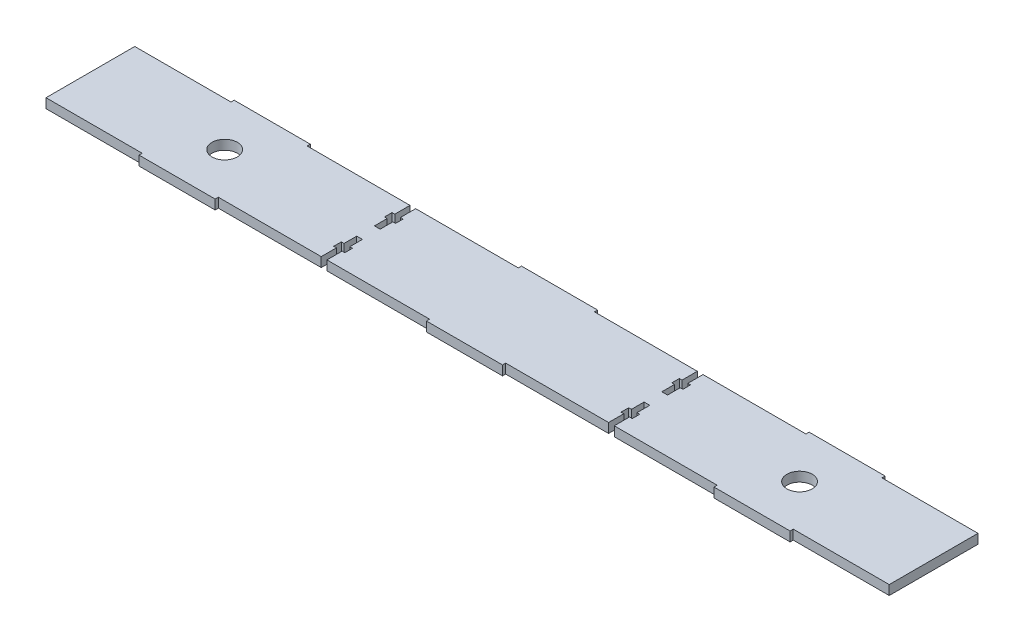
SolidWorks part; units mm, degrees
other "Markup1"
sketch "Sketch5" plane through (-211.1375, 0, -23.8125) normal (0, -1, 0) x (1, 0, 0)
ref_plane "Front Plane" through (0, 0, 0) normal (0, 0, 1) x (1, 0, 0)
ref_plane "Top Plane" through (0, 0, 0) normal (0, 1, 0) x (1, 0, 0)
ref_plane "Right Plane" through (0, 0, 0) normal (1, 0, 0) x (0, 0, -1)
sketch "Sketch1" plane through (0, 0, 0) normal (0, 1, 0) x (1, 0, 0)
  line L1 (214.3125, -23.8125) -> (-214.3125, -23.8125)
  line L2 (214.3125, -23.8125) -> (214.3125, 23.8125)
  line L3 (214.3125, 23.8125) -> (-214.3125, 23.8125)
  line L4 (-214.3125, -23.8125) -> (-214.3125, 23.8125)
  line L5 (214.3125, -23.8125) -> (-214.3125, 23.8125) construction
  line L6 (214.3125, 23.8125) -> (-214.3125, -23.8125) construction
  point P0 (0, 0)
  dimension "D1" = 428.625
  dimension "D2" = 47.625
extrude "Boss-Extrude1" add sketch "Sketch1" along normal blind 4.7625
sketch "Sketch2" plane through (0, 0, 0) normal (0, -1, 0) x (1, 0, 0)
  line L0 (74.1204, -22.225) -> (70.1516, -22.225) construction
  line L1 (-69.8976, -22.225) -> (-73.8664, -22.225) construction
  line L2 (-73.3108, 4.445) -> (-73.3108, 10.795)
  line L3 (-73.3108, 10.795) -> (-74.676, 10.795)
  line L4 (74.1204, -22.225) -> (70.1516, -22.225) construction
  line L5 (-69.8976, -22.225) -> (-73.8664, -22.225) construction
  line L6 (-162.941, 22.225) -> (-214.3125, 22.225)
  line L7 (-214.3125, -23.8125) -> (-214.3125, 23.8125) construction
  line L8 (163.068, 22.225) -> (163.068, 23.8125) construction
  line L9 (-162.941, 22.225) -> (-162.941, 23.8125) construction
  line L10 (-162.941, 23.8125) -> (-124.841, 23.8125) construction
  line L11 (-162.941, 22.225) -> (-124.841, 22.225) construction
  line L12 (-124.841, 22.225) -> (-124.841, 23.8125) construction
  line L13 (-19.05, 22.225) -> (-19.05, 23.8125) construction
  line L14 (-19.05, 23.8125) -> (19.05, 23.8125) construction
  line L15 (-19.05, 22.225) -> (19.05, 22.225) construction
  line L16 (19.05, 22.225) -> (19.05, 23.8125) construction
  line L17 (124.968, 22.225) -> (163.068, 22.225) construction
  line L18 (124.968, 23.8125) -> (163.068, 23.8125) construction
  line L19 (124.968, 22.225) -> (124.968, 23.8125) construction
  line L20 (163.068, 22.225) -> (163.068, 23.8125)
  line L21 (124.968, 22.225) -> (163.068, 22.225)
  line L22 (124.968, 23.8125) -> (163.068, 23.8125)
  line L23 (124.968, 22.225) -> (124.968, 23.8125)
  line L24 (19.05, 22.225) -> (19.05, 23.8125)
  line L25 (-19.05, 22.225) -> (19.05, 22.225)
  line L26 (-19.05, 23.8125) -> (19.05, 23.8125)
  line L27 (-19.05, 22.225) -> (-19.05, 23.8125)
  line L28 (-124.841, 22.225) -> (-124.841, 23.8125)
  line L29 (-162.941, 22.225) -> (-124.841, 22.225)
  line L30 (-162.941, 23.8125) -> (-124.841, 23.8125)
  line L31 (-162.941, 22.225) -> (-162.941, 23.8125)
  line L32 (-214.3125, 22.225) -> (-214.3125, 23.8125)
  line L33 (-214.3125, 23.8125) -> (-162.941, 23.8125)
  line L34 (-124.841, 23.8125) -> (-19.05, 23.8125)
  line L35 (-124.841, 22.225) -> (-19.05, 22.225)
  line L36 (19.05, 22.225) -> (124.968, 22.225)
  line L37 (124.968, 23.8125) -> (19.05, 23.8125)
  line L38 (163.068, 22.225) -> (214.3125, 22.225)
  line L39 (214.3125, 23.8125) -> (214.3125, -23.8125) construction
  line L40 (214.3125, 22.225) -> (214.3125, 23.8125)
  line L41 (214.3125, 23.8125) -> (163.068, 23.8125)
  line L42 (-214.3125, 0) -> (214.3125, 0) construction
  line L43 (214.3125, -22.225) -> (214.3125, -23.8125)
  line L44 (163.068, -22.225) -> (163.068, -23.8125)
  line L45 (214.3125, -23.8125) -> (163.068, -23.8125)
  line L46 (163.068, -22.225) -> (214.3125, -22.225)
  line L47 (124.968, -22.225) -> (124.968, -23.8125)
  line L48 (19.05, -22.225) -> (19.05, -23.8125)
  line L49 (124.968, -23.8125) -> (19.05, -23.8125)
  line L50 (19.05, -22.225) -> (124.968, -22.225)
  line L51 (-19.05, -22.225) -> (-19.05, -23.8125)
  line L52 (-124.841, -23.8125) -> (-19.05, -23.8125)
  line L53 (-124.841, -22.225) -> (-124.841, -23.8125)
  line L54 (-124.841, -22.225) -> (-19.05, -22.225)
  line L55 (-162.941, -22.225) -> (-162.941, -23.8125)
  line L56 (-214.3125, -22.225) -> (-214.3125, -23.8125)
  line L57 (-214.3125, -23.8125) -> (-162.941, -23.8125)
  line L58 (-162.941, -22.225) -> (-214.3125, -22.225)
  line L59 (-162.941, 22.225) -> (-162.941, 23.8125)
  line L60 (-162.941, 22.225) -> (-162.941, 23.8125)
  line L61 (-162.941, 22.225) -> (-214.3125, 22.225)
  line L62 (-214.3125, 23.8125) -> (-162.941, 23.8125)
  line L75 (-71.882, 22.225) -> (-71.882, 4.445) construction
  line L83 (-74.676, 10.795) -> (-74.676, 14.605)
  line L84 (-74.676, 14.605) -> (-73.3108, 14.605)
  line L85 (-73.3108, 14.605) -> (-73.3108, 22.225)
  line L86 (-73.3108, 22.225) -> (-70.4533, 22.225)
  line L87 (-70.4533, 4.445) -> (-73.3108, 4.445)
  line L88 (-70.4533, 4.445) -> (-70.4533, 10.795)
  line L89 (-70.4533, 10.795) -> (-69.088, 10.795)
  line L90 (-69.088, 10.795) -> (-69.088, 14.605)
  line L91 (-69.088, 14.605) -> (-70.4533, 14.605)
  line L92 (-70.4533, 14.605) -> (-70.4533, 22.225)
  line L93 (73.4377, 4.445) -> (70.5802, 4.445)
  line L94 (70.5802, 4.445) -> (70.5802, 10.795)
  line L95 (70.5802, 10.795) -> (69.215, 10.795)
  line L96 (69.215, 10.795) -> (69.215, 14.605)
  line L97 (69.215, 14.605) -> (70.5802, 14.605)
  line L98 (70.5802, 14.605) -> (70.5802, 22.225)
  line L99 (70.5802, 22.225) -> (73.4377, 22.225)
  line L100 (73.4377, 14.605) -> (73.4377, 22.225)
  line L101 (74.803, 14.605) -> (73.4377, 14.605)
  line L102 (74.803, 10.795) -> (74.803, 14.605)
  line L103 (73.4377, 10.795) -> (74.803, 10.795)
  line L104 (73.4377, 4.445) -> (73.4377, 10.795)
  line L105 (72.009, 22.225) -> (72.009, 4.445) construction
  line L106 (72.009, 13.335) -> (-71.882, 13.335) construction
  line L107 (73.4377, -4.445) -> (73.4377, -10.795)
  line L108 (73.4377, -10.795) -> (74.803, -10.795)
  line L109 (74.803, -10.795) -> (74.803, -14.605)
  line L110 (74.803, -14.605) -> (73.4377, -14.605)
  line L111 (73.4377, -14.605) -> (73.4377, -22.225)
  line L112 (70.5802, -22.225) -> (73.4377, -22.225)
  line L113 (70.5802, -14.605) -> (70.5802, -22.225)
  line L114 (69.215, -14.605) -> (70.5802, -14.605)
  line L115 (69.215, -10.795) -> (69.215, -14.605)
  line L116 (70.5802, -10.795) -> (69.215, -10.795)
  line L117 (70.5802, -4.445) -> (70.5802, -10.795)
  line L118 (73.4377, -4.445) -> (70.5802, -4.445)
  line L119 (-70.4533, -4.445) -> (-70.4533, -10.795)
  line L120 (-70.4533, -10.795) -> (-69.088, -10.795)
  line L121 (-69.088, -10.795) -> (-69.088, -14.605)
  line L122 (-69.088, -14.605) -> (-70.4533, -14.605)
  line L123 (-70.4533, -14.605) -> (-70.4533, -22.225)
  line L124 (-73.3108, -22.225) -> (-70.4533, -22.225)
  line L125 (-73.3108, -14.605) -> (-73.3108, -22.225)
  line L126 (-74.676, -14.605) -> (-73.3108, -14.605)
  line L127 (-74.676, -10.795) -> (-74.676, -14.605)
  line L128 (-73.3108, -10.795) -> (-74.676, -10.795)
  line L129 (-73.3108, -4.445) -> (-73.3108, -10.795)
  line L130 (-70.4533, -4.445) -> (-73.3108, -4.445)
  point P11 (-71.882, 23.8125)
  point P12 (72.136, 23.8125)
  point P78 (72.009, 4.445)
  line M5 (-214.3125, 23.8125) -> (-214.3125, -23.8125)
  line M6 (-214.3125, -23.8125) -> (214.3125, -23.8125)
  line M7 (214.3125, -23.8125) -> (214.3125, 23.8125)
  line M8 (214.3125, 23.8125) -> (-214.3125, 23.8125)
  dimension "D1" = 1.4287
  dimension "D2" = 17.78
  dimension "D3" = 3.81
  dimension "D4" = 5.588
  dimension "D5" = 7.62
  dimension "D6" = 2
extrude "Cut-Extrude4" cut sketch "Sketch2" against normal up to surface (4.7625 mm away) contours L54 L53 L51 M6 | L20 L38 M7 M8 | L24 L36 L23 M8 | L28 L35 L27 M8 | L50 L48 L47 M6 | L46 L44 M6 M7 | L6 L31 M8 M5 | L55 L58 M5 M6 | L119 L120 L121 L122 L123 L124 L125 L126 L127 L128 L129 L130 | L87 L2 L3 L83 L84 L85 L86 L92 L91 L90 L89 L88 | L93 L94 L95 L96 L97 L98 L99 L100 L101 L102 L103 L104 | L107 L108 L109 L110 L111 L112 L113 L114 L115 L116 L117 L118 up to face at (0, 4.7625, 0)
sketch "Sketch3" plane through (0, 0, 0) normal (0, -1, 0) x (1, 0, 0)
  line L0 (-214.3125, 0) -> (214.3125, 0) construction
  line L1 (-214.3125, -22.225) -> (-214.3125, 22.225) construction
  line L2 (214.3125, 22.225) -> (214.3125, -22.225) construction
  line L3 (-143.891, 23.8125) -> (-143.891, -23.8125) construction
  line L4 (-162.941, 23.8125) -> (-124.841, 23.8125) construction
  line L5 (-124.841, -23.8125) -> (-162.941, -23.8125) construction
  line L9 (144.018, 23.8125) -> (144.018, -23.8125) construction
  line L10 (124.968, 23.8125) -> (163.068, 23.8125) construction
  line L11 (163.068, -23.8125) -> (124.968, -23.8125) construction
  line L13 (-214.3125, -6.35) -> (214.3125, -6.35) construction
  line L15 (19.05, -22.225) -> (70.5802, -22.225) construction
  line L16 (0, 23.8125) -> (0, -23.8125) construction
  line L17 (-19.05, 23.8125) -> (19.05, 23.8125) construction
  line L18 (19.05, -23.8125) -> (-19.05, -23.8125) construction
  circle A0 centre (-143.891, 0) radius 6.35
  circle A1 centre (0, -6.35) radius 6.35 construction
  circle A2 centre (144.018, 0) radius 6.35
  dimension "D1" = 12.7
  dimension "D2" = 15.875
sketch "Sketch4" plane through (0, 0, 0) normal (0, -1, 0) x (1, 0, 0)
  line L11 (-214.3125, 0) -> (214.3125, 0) construction
  line L12 (-162.941, -22.225) -> (-214.3125, -22.225) construction
  line L13 (-214.3125, 22.225) -> (-211.1375, 22.225)
  line L14 (-214.3125, 22.225) -> (-214.3125, -22.225)
  line L15 (-214.3125, -22.225) -> (-211.1375, -22.225)
  line L16 (-211.1375, 22.225) -> (-211.1375, -22.225)
  line L21 (-214.3125, 0) -> (214.3125, 0) construction
  line L22 (0, -23.8125) -> (0, 23.8125) construction
  line L23 (-19.05, 23.8125) -> (19.05, 23.8125) construction
  line L24 (214.3125, -22.225) -> (211.1375, -22.225)
  line L25 (211.1375, 22.225) -> (211.1375, -22.225)
  line L26 (214.3125, 22.225) -> (211.1375, 22.225)
  line L27 (214.3125, 22.225) -> (214.3125, -22.225)
  point P16 (0, 0)
  dimension "D1" = 3.175
extrude "Cut-Extrude5" cut sketch "Sketch4" against normal up to surface (4.7625 mm away) up to face at (0.0535, 4.7625, 0)
extrude "Cut-Extrude6" cut sketch "Sketch3" against normal up to surface (4.7625 mm away) up to face at (0.0535, 4.7625, 0)
sketch "Sketch6" plane through (0, 0, 0) normal (0, -1, 0) x (1, 0, 0)
  line L0 (-211.1375, -22.225) -> (-211.1375, 22.225) construction
  line L1 (-162.941, 22.225) -> (-211.1375, 22.225) construction
  line L2 (163.068, 22.225) -> (211.1375, 22.225) construction
  circle A0 centre (144.018, 0) radius 6.35 construction
  circle A1 centre (-143.891, 0) radius 6.35 construction
  circle A2 centre (144.018, 0) radius 6.35
  circle A3 centre (-143.891, 0) radius 6.35
  dimension "D1" = 12.7
  dimension "D2" = 67.2465
  dimension "D3" = 22.225
  dimension "D4" = 355.1555
  dimension "D5" = 22.225
equation "\"sheetthickness\"= 3 / 16"
equation "\"D1@Boss-Extrude1\"=\"sheetthickness\""
